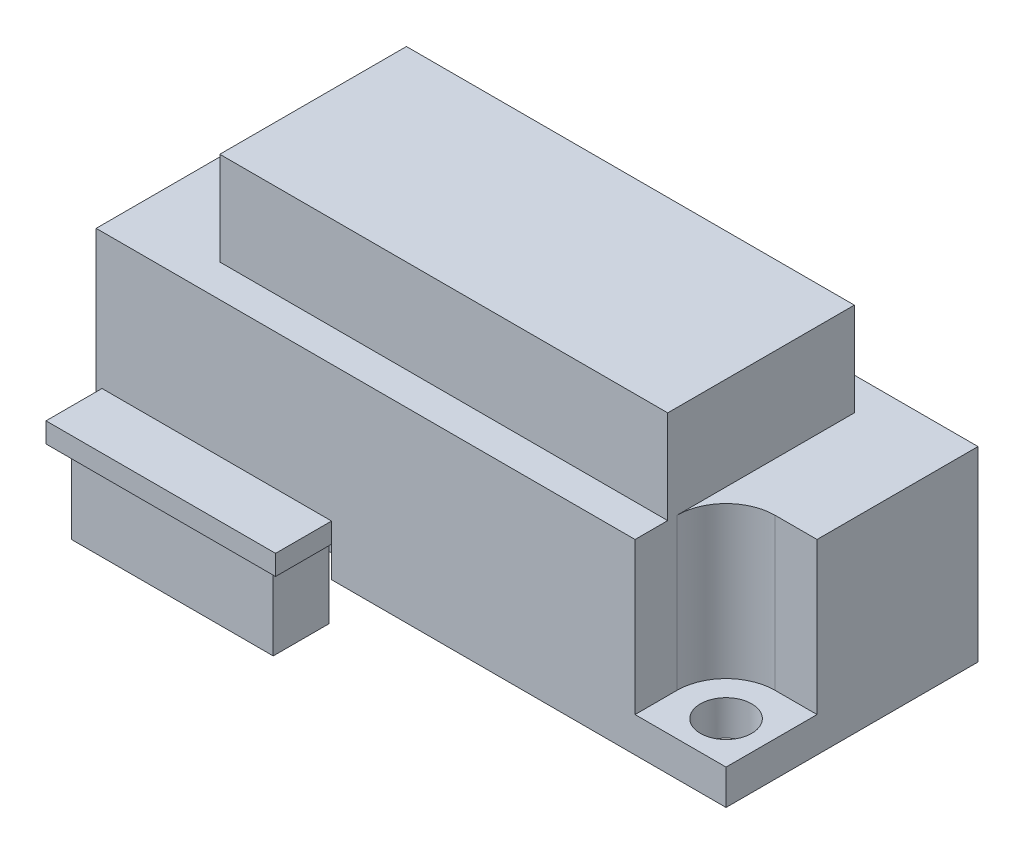
SolidWorks part; units mm, degrees
ref_plane "Front Plane" through (0, 0, 0) normal (0, 0, 1) x (1, 0, 0)
ref_plane "Top Plane" through (0, 0, 0) normal (0, 1, 0) x (1, 0, 0)
ref_plane "Right Plane" through (0, 0, 0) normal (1, 0, 0) x (0, 0, -1)
sketch "Sketch1" plane through (0, 0, 0) normal (0, 1, 0) x (1, 0, 0)
  line L1 (0, 0) -> (27, 0)
  line L2 (0, 0) -> (0, 10.8)
  line L3 (0, 10.8) -> (27, 10.8)
  line L4 (27, 0) -> (27, 10.8)
  dimension "D1" = 27
  dimension "D2" = 10.8
extrude "Boss-Extrude1" add sketch "Sketch1" along normal blind 12
sketch "Sketch2" plane through (0, 12, 0) normal (0, 1, 0) x (1, 0, 0)
  line L0 (0, 0) -> (27, 0) construction
  line L1 (0, 10.8) -> (3.9, 10.8)
  line L2 (0, 10.8) -> (0, 0)
  line L3 (0, 0) -> (3.9, 0)
  line L4 (3.9, 10.8) -> (3.9, 0)
  dimension "D1" = 3.9
extrude "Cut-Extrude1" cut sketch "Sketch2" against normal blind 4
sketch "Sketch3" plane through (0, 12, 0) normal (0, 1, 0) x (1, 0, 0)
  line L0 (3.9, 0) -> (27, 0) construction
  line L1 (27, 10.8) -> (23.1, 10.8)
  line L2 (27, 10.8) -> (27, 0)
  line L3 (27, 0) -> (23.1, 0)
  line L4 (23.1, 10.8) -> (23.1, 0)
  dimension "D1" = 3.9
extrude "Cut-Extrude2" cut sketch "Sketch3" against normal blind 4
sketch "Sketch4" plane through (0, 8, 0) normal (0, 1, 0) x (1, 0, 0)
  line L0 (27, 0) -> (27, 10.8) construction
  line L1 (23.1, 0) -> (27, 0) construction
  circle A0 centre (25.2, 1.8) radius 1.1
  point P2 (25.21, 1.7543)
  dimension "D1" = 2.2
  dimension "D2" = 1.8
  dimension "D3" = 1.8
extrude "Cut-Extrude3" cut sketch "Sketch4" against normal through all both and the other way through all
sketch "Sketch5" plane through (0, 8, 0) normal (0, 1, 0) x (1, 0, 0)
  line L1 (3.9, 10.8) -> (0, 10.8) construction
  circle A0 centre (1.8, 9) radius 1.1
  circle A1 centre (25.2, 1.8) radius 1.1 construction
  dimension "D3" = 2.2
  dimension "D1" = 23.4
  dimension "D2" = 1.8
extrude "Cut-Extrude4" cut sketch "Sketch5" against normal through all both and the other way through all
sketch "Sketch6" plane through (0, 8, 0) normal (0, 1, 0) x (1, 0, 0)
  line L0 (3.9, 0) -> (3.9, 10.8) construction
  line L1 (1.8, 6.9) -> (0, 6.9)
  line L2 (0, 10.8) -> (0, 0) construction
  line L3 (3.9, 9) -> (3.9, 10.8)
  line L4 (3.9, 10.8) -> (0, 10.8)
  line L5 (0, 10.8) -> (0, 6.9)
  line L6 (23.1, 10.8) -> (23.1, 0) construction
  line L7 (25.2, 3.9) -> (27, 3.9)
  line L8 (27, 0) -> (27, 10.8) construction
  line L9 (27, 3.9) -> (27, 0)
  line L10 (27, 0) -> (23.1, 0)
  line L11 (23.1, 0) -> (23.1, 1.8)
  arc A0 (3.9, 9) -> (1.8, 6.9) centre (1.8, 9) cw
  arc A1 (23.1, 1.8) -> (25.2, 3.9) centre (25.2, 1.8) cw
  dimension "D1" = 3.9
extrude "Cut-Extrude5" cut sketch "Sketch6" against normal blind 6.5
sketch "Sketch7" plane through (0, 12, 0) normal (0, 1, 0) x (1, 0, 0)
  line L0 (3.9, 0) -> (3.9, 10.8) construction
  line L1 (3.9, 9.4) -> (23.1, 9.4)
  line L2 (3.9, 9.4) -> (3.9, 1.4)
  line L3 (3.9, 1.4) -> (23.1, 1.4)
  line L4 (23.1, 9.4) -> (23.1, 1.4)
  line L5 (23.1, 10.8) -> (23.1, 0) construction
  line L6 (23.1, 10.8) -> (3.9, 10.8) construction
  dimension "D1" = 8
  dimension "D2" = 1.4
extrude "Cut-Extrude6" cut sketch "Sketch7" against normal up to surface (4 mm away) flip side to cut up to face at (24.993, 8, -6.327)
sketch "Sketch8" plane through (0, 0, 0) normal (0, -1, 0) x (1, 0, 0)
  line L1 (0.25, -1) -> (10.09, -1)
  line L2 (0.25, -1) -> (0.25, 2.4)
  line L3 (0.25, 2.4) -> (10.09, 2.4)
  line L4 (10.09, -1) -> (10.09, 2.4)
  line L5 (0, 0) -> (27, 0) construction
  line L6 (0, -10.8) -> (0, 0) construction
  line L7 (27, -10.8) -> (0, -10.8) construction
  point P4 (0.2584, -1)
  point P8 (0, 0)
  dimension "D1" = 9.84
  dimension "D2" = 13.2
  dimension "D3" = 1
  dimension "D4" = 0.25
extrude "Boss-Extrude2" add sketch "Sketch8" along normal blind 2.18 and the other way blind 2.18
sketch "Sketch9" plane through (0, -2.18, 0) normal (0, -1, 0) x (1, 0, 0)
  line L1 (9.49, 1.9) -> (0.85, 1.9)
  line L2 (9.49, 1.9) -> (9.49, -0.5)
  line L3 (9.49, -0.5) -> (0.85, -0.5)
  line L4 (0.85, 1.9) -> (0.85, -0.5)
  line L9 (10.09, -1) -> (0.25, -1)
  line L10 (10.09, -1) -> (10.09, 2.4)
  line L11 (10.09, 2.4) -> (0.25, 2.4)
  line L12 (0.25, -1) -> (0.25, 2.4)
  dimension "D1" = 0.5
  dimension "D2" = 0.5
  dimension "D3" = 0.6
  dimension "D4" = 0.6
extrude "Cut-Extrude7" cut sketch "Sketch9" against normal blind 3.5
